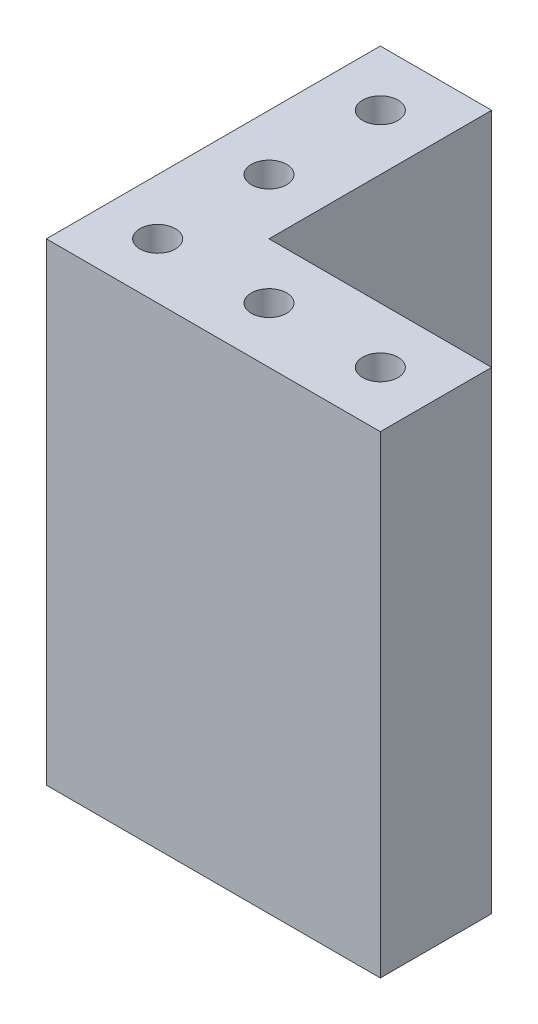
SolidWorks part; units mm, degrees
material "6061-T6 (SS)"
ref_plane "Front Plane" through (0, 0, 0) normal (0, 0, 1) x (1, 0, 0)
ref_plane "Top Plane" through (0, 0, 0) normal (0, 1, 0) x (1, 0, 0)
ref_plane "Right Plane" through (0, 0, 0) normal (1, 0, 0) x (0, 0, -1)
sketch "Sketch1" plane through (0, 0, 0) normal (0, 1, 0) x (1, 0, 0)
  line L0 (-6.35, -6.35) -> (31.75, -6.35)
  line L1 (-6.35, -6.35) -> (-6.35, 31.75)
  line L2 (31.75, -6.35) -> (31.75, 6.35)
  line L3 (31.75, 6.35) -> (6.35, 6.35)
  line L4 (6.35, 6.35) -> (6.35, 31.75)
  line L5 (6.35, 31.75) -> (-6.35, 31.75)
  circle A0 centre (0, 0) radius 2.0193
  circle A1 centre (12.7, 0) radius 2.0193
  circle A2 centre (25.4, 0) radius 2.0193
  circle A3 centre (12.7, 12.7) radius 2.0193 construction
  circle A4 centre (25.4, 12.7) radius 2.0193 construction
  circle A5 centre (12.7, 25.4) radius 2.0193 construction
  circle A6 centre (25.4, 25.4) radius 2.0193 construction
  circle A7 centre (0, 12.7) radius 2.0193
  circle A8 centre (0, 25.4) radius 2.0193
  dimension "D1" = 4.0386
  dimension "D2" = 6.35
  dimension "D3" = 6.35
  dimension "D6" = 12.7
  dimension "D7" = 12.7
  dimension "D8" = 38.1
  dimension "D9" = 12.7
  dimension "D10" = 12.7
  dimension "D4" = 3
  dimension "D5" = 3
extrude "Boss-Extrude1" add sketch "Sketch1" along normal blind 53.975
